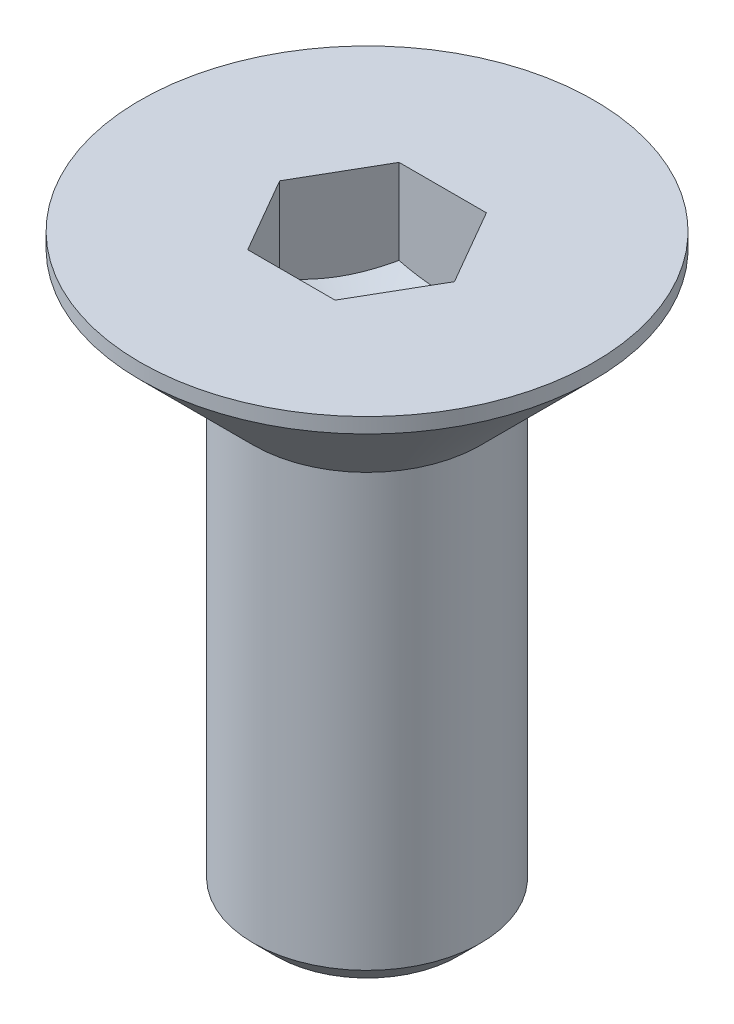
SolidWorks part; units mm, degrees
ref_plane "Front Plane" through (0, 0, 0) normal (0, 0, 1) x (1, 0, 0)
ref_plane "Top Plane" through (0, 0, 0) normal (0, 1, 0) x (1, 0, 0)
ref_plane "Right Plane" through (0, 0, 0) normal (1, 0, 0) x (0, 0, -1)
sketch "Sketch1" plane through (0, 0, 0) normal (0, 0, 1) x (1, 0, 0)
  line L3 (-1.5, -1.7) -> (-1.5, -7.4)
  line L5 (0, 2.75) -> (0, -11.9483) construction
  line L7 (-3, 0) -> (-1, 0)
  line L8 (-1, 0) -> (-1, -1.2)
  line L9 (-1, -1.2) -> (0, -1.7)
  line L10 (-1.2, -7.7) -> (0, -7.7)
  line L11 (-1.5, -7.4) -> (-1.2, -7.7)
  line L12 (0, -1.7) -> (0, -7.7)
  line L14 (-3, 0) -> (-3, -0.2)
  line L15 (-3, -0.2) -> (-1.5, -1.7)
  point P0 (-1.5, -2.0196)
  point P15 (-1.5, -7.7)
  dimension "D5" = 1.7
  dimension "D6" = 6
  dimension "D1" = 2
  dimension "D2" = 6
  dimension "D3" = 45
  dimension "D4" = 3
  dimension "D7" = 1.2
  dimension "D8" = 0.5
revolve "Revolve1" add sketch "Sketch1" angle 360 about L5
sketch "Sketch3" plane through (0, 0, 0) normal (0, 1, 0) x (1, 0, 0)
  line L1 (-0.5774, -1) -> (0.5774, -1)
  line L2 (0.5774, -1) -> (1.1547, 0)
  line L3 (1.1547, 0) -> (0.5774, 1)
  line L4 (0.5774, 1) -> (-0.5774, 1)
  line L5 (-0.5774, 1) -> (-1.1547, 0)
  line L6 (-1.1547, 0) -> (-0.5774, -1)
  circle A0 centre (0, 0) radius 1 construction
  circle A1 centre (0, 0) radius 1 construction
extrude "Cut-Extrude2" cut sketch "Sketch3" against normal up to surface (1.1226 mm away)
